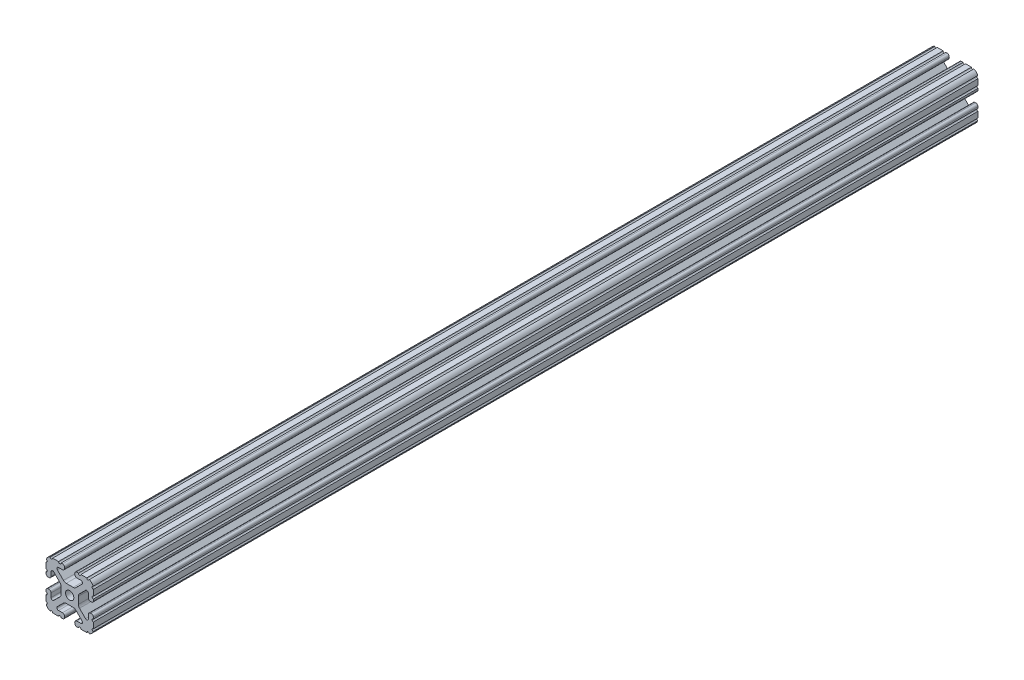
SolidWorks part; units mm, degrees
ref_plane "Front Plane" through (0, 0, 0) normal (0, 0, 1) x (1, 0, 0)
ref_plane "Top Plane" through (0, 0, 0) normal (0, 1, 0) x (1, 0, 0)
ref_plane "Right Plane" through (0, 0, 0) normal (1, 0, 0) x (0, 0, -1)
sketch "Sketch2" plane through (0, 0, 0) normal (0, 0, 1) x (1, 0, 0)
  line L0 (0, 19.05) -> (0, -19.05) construction
  line L1 (-19.05, 0) -> (19.05, 0) construction
  line L2 (4.064, -19.05) -> (19.05, -19.05)
  line L3 (19.05, -19.05) -> (19.05, -4.064)
  line L4 (4.064, -19.05) -> (4.064, -14.986)
  line L5 (4.064, -14.986) -> (12.1123, -14.986)
  line L6 (12.1123, -14.986) -> (4.1113, -6.985)
  line L7 (0, 0) -> (19.05, -19.05) construction
  line L8 (19.05, -4.064) -> (14.986, -4.064)
  line L9 (14.986, -4.064) -> (14.986, -12.1123)
  line L10 (14.986, -12.1123) -> (6.985, -4.1113)
  circle A0 centre (0, 0) radius 3.3274
  arc A1 (8.9963, -14.986) -> (9.909, -12.7826) centre (8.9963, -13.6953) ccw construction
  point P8 (0, -6.985)
  dimension "Center Hole Diameter" = 6.6548
  dimension "Rail Height" = 38.1
  dimension "Rail Width" = 38.1
  dimension "T-Slot Width" = 8.128
  dimension "Slot Inner Width" = 20.574
  dimension "Thickness" = 4.064
  dimension "Slot Depth" = 8.001
  dimension "D1" = 4.064
sketch "Sketch3" plane through (0, 0, 0) normal (1, 0, 0) x (0, 0, -1)
  line L0 (-152.4, -19.05) -> (152.4, -19.05) construction
  line L1 (-127, 0) -> (127, 0) construction
  dimension "Length" = 304.8
  dimension "D1" = 25.4
sketch "Sketch4" plane through (0, 0, 0) normal (0, 0, 1) x (1, 0, 0)
  line L0 (5.7912, -19.05) -> (14.3002, -19.05)
  line L1 (4.064, -19.05) -> (19.05, -19.05) construction
  line L2 (4.064, -19.05) -> (4.064, -14.986) construction
  line L3 (4.064, -14.986) -> (12.1123, -14.986) construction
  line L4 (4.064, -16.7132) -> (4.064, -17.3228)
  line L5 (5.7912, -14.986) -> (8.9963, -14.986)
  line L6 (0, -6.985) -> (2.833, -6.985)
  line L7 (12.1123, -14.986) -> (4.1113, -6.985) construction
  line L8 (5.0152, -7.8889) -> (9.909, -12.7826)
  line L9 (19.05, -19.05) -> (19.05, -4.064) construction
  line L10 (14.986, -12.1123) -> (6.985, -4.1113) construction
  line L11 (14.986, -4.064) -> (14.986, -12.1123) construction
  line L12 (14.986, -8.9963) -> (14.986, -5.7912)
  line L13 (19.05, -4.064) -> (14.986, -4.064) construction
  line L14 (16.7132, -4.064) -> (17.3228, -4.064)
  line L15 (19.05, -5.7912) -> (19.05, -14.3002)
  line L16 (12.7826, -9.909) -> (7.8889, -5.0152)
  line L17 (6.985, 0) -> (6.985, -2.833)
  line L18 (-19.05, 0) -> (19.05, 0) construction
  line L19 (0, -6.985) -> (0, -3.3274)
  line L20 (0, 19.05) -> (0, -19.05) construction
  line L21 (6.985, 0) -> (3.3274, 0)
  arc A0 (4.064, -17.3228) -> (5.7912, -19.05) centre (5.7912, -17.3228) ccw
  arc A2 (4.064, -16.7132) -> (5.7912, -14.986) centre (5.7912, -16.7132) cw
  arc A3 (8.9963, -14.986) -> (9.909, -12.7826) centre (8.9963, -13.6953) ccw
  arc A4 (2.833, -6.985) -> (5.0152, -7.8889) centre (2.833, -10.0711) cw
  arc A5 (14.3002, -19.05) -> (19.05, -14.3002) centre (14.3002, -14.3002) ccw
  arc A6 (12.7826, -9.909) -> (14.986, -8.9963) centre (13.6953, -8.9963) ccw
  arc A7 (14.986, -5.7912) -> (16.7132, -4.064) centre (16.7132, -5.7912) cw
  arc A8 (17.3228, -4.064) -> (19.05, -5.7912) centre (17.3228, -5.7912) cw
  arc A9 (7.8889, -5.0152) -> (6.985, -2.833) centre (10.0711, -2.833) cw
  circle A10 centre (0, 0) radius 3.3274 construction
  arc A11 (0, -3.3274) -> (3.3274, 0) centre (0, 0) ccw
  dimension "D1" = 4.7498
  dimension "D2" = 3.0861
  dimension "D3" = 1.7272
extrude "Boss-Extrude1" add sketch "Sketch4" along normal mid plane 711.2
sketch "Sketch5" plane through (0, 0, 0) normal (0, 0, 1) x (1, 0, 0)
  line L0 (4.064, -19.05) -> (19.05, -19.05) construction
  line L1 (5.7912, -14.986) -> (8.9963, -14.986) construction
  line L3 (0, 0) -> (19.05, -19.05) construction
  line L4 (8.9963, -14.986) -> (8.9963, -19.05) construction
  line L5 (12.1123, -14.986) -> (4.1113, -6.985) construction
  circle A0 centre (14.7395, -19.05) radius 1.016
  circle A1 centre (7.9803, -19.05) radius 1.016
  circle A2 centre (19.05, -14.7395) radius 1.016
  circle A3 centre (19.05, -7.9803) radius 1.016
  point P10 (7.3938, -14.986)
  point P12 (13.6953, -8.9963)
extrude "Cut-Extrude1" cut sketch "Sketch5" against normal through all both and the other way through all
mirror "Mirror1" about plane through (0, 0, 0) normal (1, 0, 0) of bodies 137 134
mirror "Mirror2" about plane through (0, 0, 0) normal (0, 1, 0) of bodies 135
equation "\"D1@Boss-Extrude1\"=\"Length@Sketch3\""
equation "\"D1@Sketch2\"=\"Thickness@Sketch2\""
equation "\"D2@Sketch4\"=\"Slot Inner Width@Sketch2\"*0.15"
equation "\"D1@Sketch4\"=\"D3@Sketch4\"*2.75"
equation "\"D3@Sketch4\"=\"Thickness@Sketch2\"*0.425"
equation "\"D1@Sketch5\"=\"Thickness@Sketch2\"*0.5"
